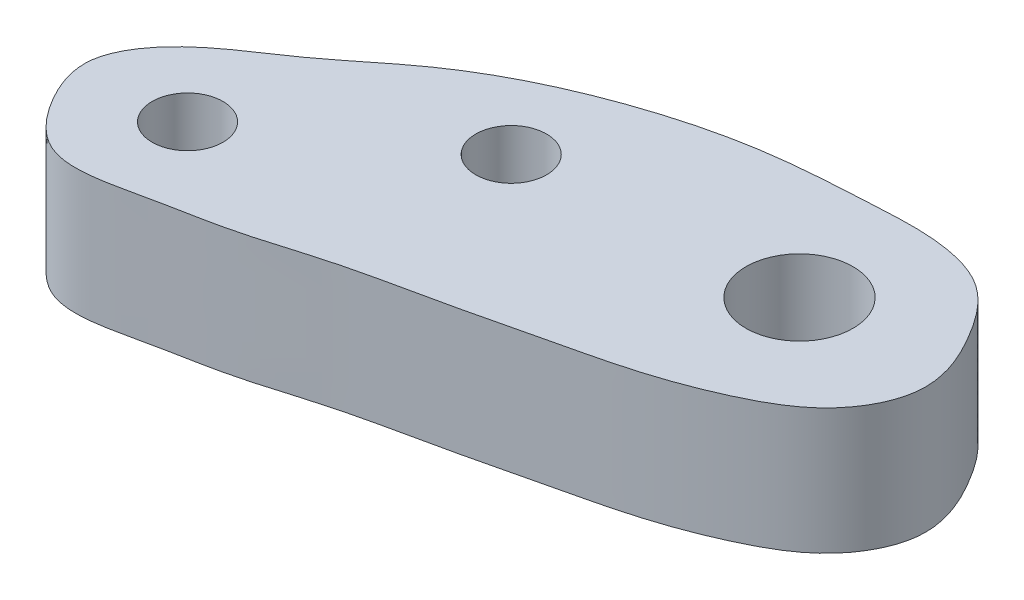
SolidWorks part; units mm, degrees
ref_plane "Front Plane" through (0, 0, 0) normal (0, 0, 1) x (1, 0, 0)
ref_plane "Top Plane" through (0, 0, 0) normal (0, 1, 0) x (1, 0, 0)
ref_plane "Right Plane" through (0, 0, 0) normal (1, 0, 0) x (0, 0, -1)
sketch "Sketch1" plane through (0, 0, 0) normal (0, 1, 0) x (1, 0, 0)
  line L0 (47.2297, 219.0186) -> (732.563, 219.0186) construction
  circle A0 centre (-3.1153, 44.686) radius 1.7
  circle A1 centre (-11.6313, 44.0427) radius 1.125
  circle A2 centre (-17.6686, 39.7977) radius 1.125
  spline S0 degree 3 poles (-21.1628, 39.9043) (-19.961, 41.9595) (-17.6936, 43.2143) (-14.9987, 45.5967) (-11.5563, 47.2555) (-7.8342, 48.2324) (-4.9683, 48.3726) (-2.6679, 48.5042) (-0.6253, 48.1169) (0.7469, 46.2969) (1.7234, 44.1539) (0.5453, 41.9841) (-1.4575, 40.8322) (-3.6767, 40.0172) (-6.1543, 39.4776) (-8.7562, 38.8208) (-11.3934, 38.3189) (-13.9291, 37.4726) (-16.3498, 37.0867) (-18.963, 36.3857) (-20.4926, 38.1653) (-21.1628, 39.9043) (-19.961, 41.9595) (-17.6936, 43.2143) knots -0.09674 -0.062266 -0.028325 0 0.060777 0.115208 0.200384 0.271361 0.329362 0.359805 0.401542 0.437504 0.48367 0.523382 0.56154 0.611495 0.655146 0.70323 0.761511 0.805502 0.851029 0.90326 0.937734 0.971675 1 1.060777 1.115208 1.200384 only from (-20.2237, 41.3458) to (-20.2237, 41.3458)
extrude "Boss-Extrude2" add sketch "Sketch1" along normal blind 4
